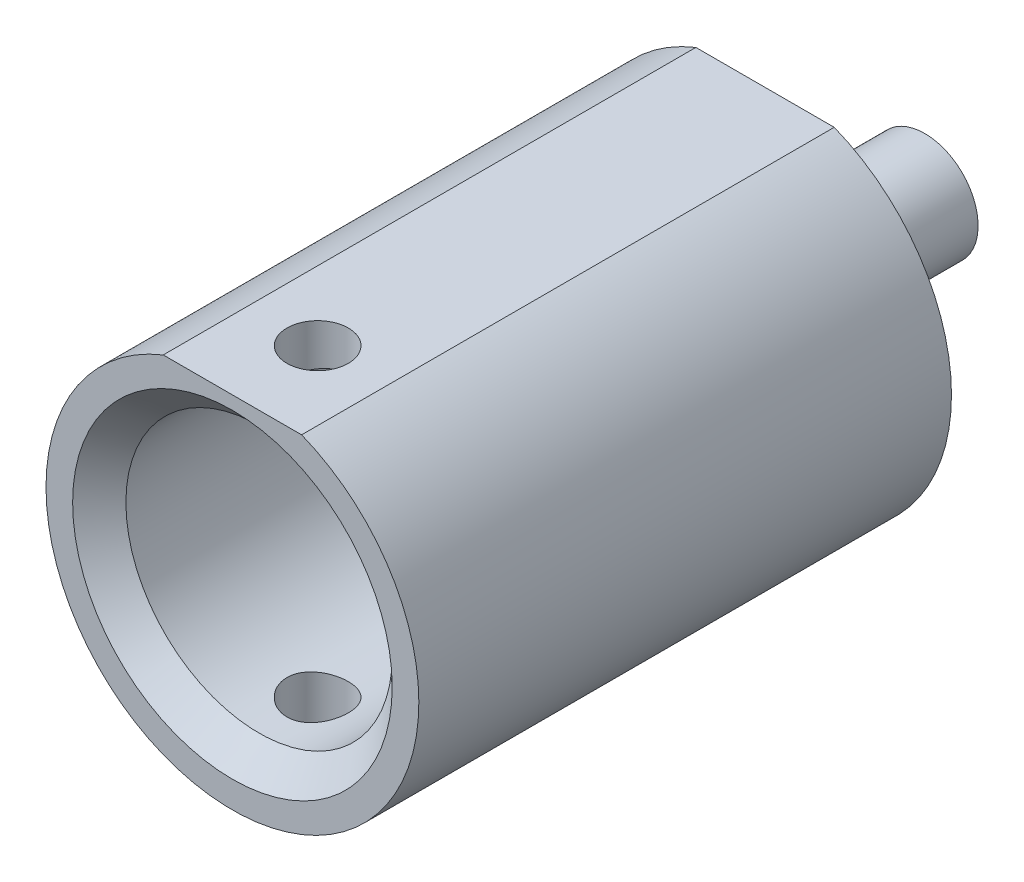
SolidWorks part; units mm, degrees
ref_plane "Front Plane" through (0, 0, 0) normal (0, 0, 1) x (1, 0, 0)
ref_plane "Top Plane" through (0, 0, 0) normal (0, 1, 0) x (1, 0, 0)
ref_plane "Right Plane" through (0, 0, 0) normal (1, 0, 0) x (0, 0, -1)
sketch "Sketch1" plane through (0, 0, 0) normal (0, 1, 0) x (1, 0, 0)
  line L6 (0, 0) -> (7.9375, 0)
  line L7 (7.9375, 0) -> (11.1125, 0)
  line L8 (11.1125, 0) -> (11.1125, 31.75)
  line L9 (11.1125, 31.75) -> (3.175, 31.75)
  line L10 (3.175, 31.75) -> (3.175, 41.275)
  line L11 (3.175, 41.275) -> (0, 41.275)
  line L12 (0, 41.275) -> (0, 25.4)
  line L13 (0, 25.4) -> (0, 0)
  line L14 (0, 25.4) -> (7.9375, 25.4) construction
  line L15 (7.9375, 25.4) -> (7.9375, 0) construction
  dimension "D1" = 3.175
  dimension "D2" = 7.9375
  dimension "D3" = 6.35
  dimension "D4" = 25.4
  dimension "D5" = 9.525
revolve "Revolve1" add sketch "Sketch1" angle 360 about L13
hole_wizard "5/8 (0.625) Diameter Hole1" positions "Sketch6" profile "Sketch7" hole size "5/8" standard "ANSI Inch"
sketch "Sketch6" plane through (0, 0, 0) normal (0, 0, 1) x (1, 0, 0)
  point P0 (0, 0)
sketch "Sketch7" plane through (0, 0, 0) normal (1, 0, 0) x (0, -1, 0)
  line L0 (0, 0) -> (0, 30.1693)
  line L1 (0, 30.1693) -> (7.9375, 25.4)
  line L2 (7.9375, 25.4) -> (7.9375, 0)
  line L5 (7.9375, 0) -> (0, 0)
  line L10 (0, 30.1693) -> (-7.9375, 25.4) construction
  line L11 (0, -6.35) -> (0, 107.95) construction
  dimension "Hole Dia." = 15.875
  dimension "Hole Depth" = 25.4
  dimension "Drill Angle" = 118
sketch "Sketch3" plane through (0, 0, 0) normal (1, 0, 0) x (0, 0, -1)
  line L0 (0, 10.3188) -> (0, 11.1125)
  line L1 (0, 11.1125) -> (0, -11.1125) construction
  line L2 (0, 11.1125) -> (31.75, 11.1125)
  line L3 (31.75, 11.1125) -> (31.75, 10.3188)
  line L4 (31.75, -11.1125) -> (31.75, 11.1125) construction
  line L5 (31.75, 10.3188) -> (0, 10.3188)
  dimension "D1" = 0.7937
extrude "Cut-Extrude1" cut sketch "Sketch3" against normal through all both and the other way through all
hole_wizard "#6 Clearance Hole1" positions "Sketch4" profile "Sketch5" hole size "#6" standard "ANSI Inch" end condition through all
sketch "Sketch4" plane through (0, 10.3188, 0) normal (0, 1, 0) x (1, 0, 0)
  line L1 (7.9375, 25.4) -> (-7.9375, 25.4) construction
  point P0 (0, 5.08)
  point P12 (-1.6561, 34.5075)
  dimension "D1" = 20.32
sketch "Sketch5" plane through (0, 10.3188, -5.08) normal (1, 0, 0) x (0, 0, 1)
  line L0 (0, 0) -> (0, 21.4313)
  line L1 (0, 21.4313) -> (1.8288, 21.4313)
  line L2 (1.8288, 21.4313) -> (1.8288, 0)
  line L5 (1.8288, 0) -> (0, 0)
  line L11 (0, -6.35) -> (0, 107.95) construction
  dimension "Thru Hole Dia." = 3.6576
  dimension "Thru Hole Depth" = 21.4313
chamfer "Chamfer1" distance 1.5875 angle 45 1 edges at (7.9375, 0, 0)
